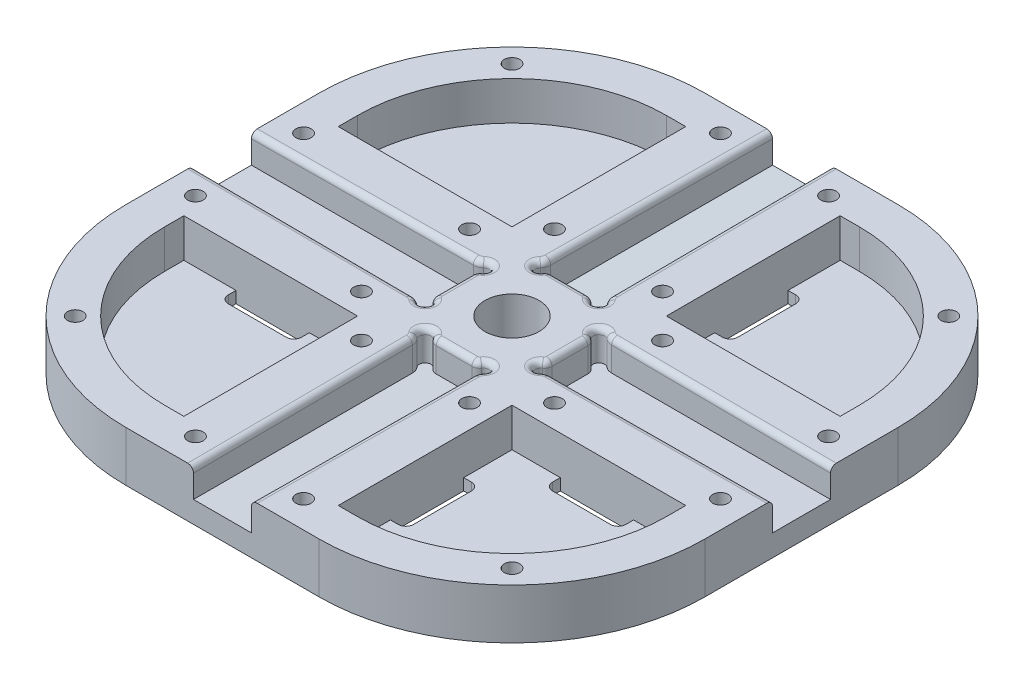
SolidWorks part; units mm, degrees
ref_plane "Front Plane" through (0, 0, 0) normal (0, 0, 1) x (1, 0, 0)
ref_plane "Top Plane" through (0, 0, 0) normal (0, 1, 0) x (1, 0, 0)
ref_plane "Right Plane" through (0, 0, 0) normal (1, 0, 0) x (0, 0, -1)
sketch "Sketch1" plane through (0, 0, 0) normal (0, 1, 0) x (1, 0, 0)
  line L1 (-25, 75) -> (25, 75)
  line L2 (-75, 25) -> (-75, -25)
  line L3 (-25, -75) -> (25, -75)
  line L4 (75, 25) -> (75, -25)
  line L5 (-75, 75) -> (75, -75) construction
  line L6 (-75, -75) -> (75, 75) construction
  arc A0 (-75, -25) -> (-25, -75) centre (-25, -25) ccw
  arc A1 (25, -75) -> (75, -25) centre (25, -25) ccw
  arc A2 (25, 75) -> (75, 25) centre (25, 25) cw
  arc A3 (-25, 75) -> (-75, 25) centre (-25, 25) ccw
  point P0 (0, 0)
  dimension "D3" = 50
  dimension "D1" = 150
  dimension "D2" = 150
extrude "Base-Extrude1" add sketch "Sketch1" along normal blind 13
sketch "Sketch2" plane through (0, 13, 0) normal (0, 1, 0) x (1, 0, 0)
  line L0 (75, 7.5) -> (75, -7.5)
  line L1 (75, 7.5) -> (18.4641, 7.5)
  line L2 (18.4641, 7.5) -> (16.5, 7.5)
  line L3 (0, 75) -> (0, -75) construction
  line L4 (25, 75) -> (-25, 75) construction
  line L5 (-25, -75) -> (25, -75) construction
  line L6 (15, 4.6277) -> (15, -4.6277)
  line L7 (-7.5, 75) -> (7.5, 75)
  line L8 (-7.5, 75) -> (-7.5, 18.4641)
  line L9 (-4.6277, 15) -> (4.6277, 15)
  line L10 (7.5, 75) -> (7.5, 18.4641)
  line L11 (18.4641, -7.5) -> (16.5, -7.5)
  line L12 (75, -7.5) -> (18.4641, -7.5)
  line L13 (7.5, -75) -> (-7.5, -75)
  line L14 (7.5, -75) -> (7.5, -18.4641)
  line L15 (7.5, -18.4641) -> (7.5, -16.5)
  line L16 (4.6277, -15) -> (-4.6277, -15)
  line L17 (-7.5, -18.4641) -> (-7.5, -16.5)
  line L18 (-7.5, -75) -> (-7.5, -18.4641)
  line L19 (-7.5, 18.4641) -> (-7.5, 16.5)
  line L20 (7.5, 18.4641) -> (7.5, 16.5)
  line L21 (-75, -7.5) -> (-75, 7.5)
  line L22 (-75, -7.5) -> (-18.4641, -7.5)
  line L23 (-18.4641, -7.5) -> (-16.5, -7.5)
  line L24 (-15, -4.6277) -> (-15, 4.6277)
  line L25 (-18.4641, 7.5) -> (-16.5, 7.5)
  line L26 (-75, 7.5) -> (-18.4641, 7.5)
  arc A0 (6.269, 14.1429) -> (7.5, 16.5) centre (7.5, 15) ccw
  arc A1 (-6.269, 14.1429) -> (-7.5, 16.5) centre (-7.5, 15) cw
  arc A2 (6.269, 14.1429) -> (4.6277, 15) centre (4.6277, 13) ccw
  arc A3 (14.1429, 6.269) -> (16.5, 7.5) centre (15, 7.5) cw
  arc A4 (14.1429, 6.269) -> (15, 4.6277) centre (13, 4.6277) cw
  arc A5 (-6.269, 14.1429) -> (-4.6277, 15) centre (-4.6277, 13) cw
  arc A6 (14.1429, -6.269) -> (15, -4.6277) centre (13, -4.6277) ccw
  arc A7 (14.1429, -6.269) -> (16.5, -7.5) centre (15, -7.5) ccw
  arc A8 (6.269, -14.1429) -> (7.5, -16.5) centre (7.5, -15) cw
  arc A9 (6.269, -14.1429) -> (4.6277, -15) centre (4.6277, -13) cw
  arc A10 (-6.269, -14.1429) -> (-4.6277, -15) centre (-4.6277, -13) ccw
  arc A11 (-6.269, -14.1429) -> (-7.5, -16.5) centre (-7.5, -15) ccw
  arc A12 (-14.1429, -6.269) -> (-16.5, -7.5) centre (-15, -7.5) cw
  arc A13 (-14.1429, -6.269) -> (-15, -4.6277) centre (-13, -4.6277) cw
  arc A14 (-14.1429, 6.269) -> (-15, 4.6277) centre (-13, 4.6277) ccw
  arc A15 (-14.1429, 6.269) -> (-16.5, 7.5) centre (-15, 7.5) ccw
  point P17 (6, 15)
  point P20 (7.5, 16.5)
  point P23 (-7.5, 16.5)
  point P26 (-6, 15)
  point P69 (0, 0)
  dimension "D3" = 3
  dimension "D4" = 2
  dimension "D1" = 60
  dimension "D2" = 15
  dimension "D5" = 4
extrude "TubePlace-Cut" cut sketch "Sketch2" against normal blind 7.4
draft "Draft3" type of draft neutral plane draft angle 0.4 faces to draft 3 face at (0, 5.6, 29.9571) face at (-7.5, 9.3, 45.75) face at (7.5, 9.3, 45.75) neutral plane through (-25, 13, 75) neutral plane normal (0, 0, 1) reverse direction yes parameters "D1"=0.4
draft "Draft4" type of draft neutral plane draft angle 0.4 faces to draft 3 face at (45.75, 9.3, 7.5) face at (45.75, 9.3, -7.5) face at (29.9571, 5.6, 0) neutral plane through (75, 13, -25) neutral plane normal (1, 0, 0) reverse direction yes parameters "D1"=0.4
draft "Draft5" type of draft neutral plane draft angle 0.4 faces to draft 3 face at (7.5, 9.3, -45.75) face at (0, 5.6, -29.9571) face at (-7.5, 9.3, -45.75) neutral plane through (-25, 13, -75) neutral plane normal (0, 0, -1) reverse direction yes parameters "D1"=0.4
draft "Draft6" type of draft neutral plane draft angle 0.4 faces to draft 3 face at (-29.9571, 5.6, 0) face at (-45.75, 9.3, -7.5) face at (-45.75, 9.3, 7.5) neutral plane through (-75, 13, -25) neutral plane normal (-1, 0, 0) reverse direction yes parameters "D1"=0.4
sketch "Sketch3" plane through (0, 13, 0) normal (0, 1, 0) x (1, 0, 0)
  line L0 (0, 75) -> (0, -75) construction
  line L1 (7.5, 75) -> (-7.5, 75) construction
  line L2 (-7.5, -75) -> (7.5, -75) construction
  line L3 (-75, 0) -> (75, 0) construction
  line L8 (-75, 7.5) -> (-75, -7.5) construction
  line L9 (75, -7.5) -> (75, 7.5) construction
  line L10 (-25, 65) -> (-20, 65)
  line L11 (-20, 65) -> (-20, 20)
  line L14 (-20, 20) -> (-65, 20)
  line L15 (-65, 20) -> (-65, 25)
  line L16 (20, 65) -> (25, 65)
  line L17 (20, 20) -> (20, 65)
  line L18 (65, 20) -> (20, 20)
  line L19 (65, 25) -> (65, 20)
  line L20 (65, -20) -> (65, -25)
  line L21 (20, -20) -> (65, -20)
  line L22 (20, -65) -> (20, -20)
  line L23 (25, -65) -> (20, -65)
  line L24 (-20, -65) -> (-25, -65)
  line L25 (-20, -20) -> (-20, -65)
  line L26 (-65, -20) -> (-20, -20)
  line L27 (-65, -25) -> (-65, -20)
  arc A1 (65, 25) -> (25, 65) centre (25, 25) ccw
  arc A2 (-25, 65) -> (-65, 25) centre (-25, 25) ccw
  arc A3 (-25, 65) -> (-65, 25) centre (-25, 25) ccw
  arc A4 (25, -65) -> (65, -25) centre (25, -25) ccw
  arc A5 (-65, -25) -> (-25, -65) centre (-25, -25) ccw
  circle A6 centre (0, 0) radius 7
  point P39 (0, 0)
  dimension "D5" = 14
  dimension "D2" = 20
  dimension "D3" = 20
  dimension "D1" = 10
  dimension "D4" = 4
extrude "Cut-Extrude2" cut sketch "Sketch3" against normal blind 10
sketch "Sketch4" plane through (0, 3, 0) normal (0, 1, 0) x (1, 0, 0)
  line L0 (-75, 0) -> (75, 0) construction
  line L1 (-75, 7.5) -> (-75, -7.5) construction
  line L2 (75, -7.5) -> (75, 7.5) construction
  line L3 (-22, 49.5) -> (-22, 34.5) construction
  line L4 (-20, 51.5) -> (-20, 32.5)
  line L5 (-24, 49.5) -> (-24, 34.5)
  line L6 (0, 75) -> (0, -75) construction
  line L7 (7.5, 75) -> (-7.5, 75) construction
  line L8 (-7.5, -75) -> (7.5, -75) construction
  line L9 (-20, 20) -> (-20, 65) construction
  line L10 (-22, 51.5) -> (-20, 51.5)
  line L11 (-20, 20) -> (-20, 65) construction
  line L12 (-22, 32.5) -> (-20, 32.5)
  line L13 (0, 0) -> (-53.2843, 53.2843) construction
  line L14 (-51.5, 20) -> (-32.5, 20)
  line L15 (-32.5, 22) -> (-32.5, 20)
  line L16 (-49.5, 24) -> (-34.5, 24)
  line L17 (-51.5, 22) -> (-51.5, 20)
  line L18 (51.5, 22) -> (51.5, 20)
  line L19 (51.5, 20) -> (32.5, 20)
  line L20 (32.5, 22) -> (32.5, 20)
  line L21 (49.5, 24) -> (34.5, 24)
  line L22 (24, 49.5) -> (24, 34.5)
  line L23 (22, 51.5) -> (20, 51.5)
  line L24 (20, 51.5) -> (20, 32.5)
  line L25 (22, 32.5) -> (20, 32.5)
  line L26 (22, -51.5) -> (20, -51.5)
  line L27 (20, -51.5) -> (20, -32.5)
  line L28 (22, -32.5) -> (20, -32.5)
  line L29 (24, -49.5) -> (24, -34.5)
  line L30 (49.5, -24) -> (34.5, -24)
  line L31 (51.5, -22) -> (51.5, -20)
  line L32 (51.5, -20) -> (32.5, -20)
  line L33 (32.5, -22) -> (32.5, -20)
  line L34 (-51.5, -22) -> (-51.5, -20)
  line L35 (-51.5, -20) -> (-32.5, -20)
  line L36 (-32.5, -22) -> (-32.5, -20)
  line L37 (-49.5, -24) -> (-34.5, -24)
  line L38 (-24, -49.5) -> (-24, -34.5)
  line L39 (-22, -51.5) -> (-20, -51.5)
  line L40 (-20, -51.5) -> (-20, -32.5)
  line L41 (-22, -32.5) -> (-20, -32.5)
  arc A0 (-22, 51.5) -> (-24, 49.5) centre (-22, 49.5) ccw
  arc A1 (-24, 34.5) -> (-22, 32.5) centre (-22, 34.5) ccw
  arc A2 (-25, 65) -> (-65, 25) centre (-25, 25) ccw construction
  arc A3 (-34.5, 24) -> (-32.5, 22) centre (-34.5, 22) cw
  arc A4 (-51.5, 22) -> (-49.5, 24) centre (-49.5, 22) cw
  arc A5 (51.5, 22) -> (49.5, 24) centre (49.5, 22) ccw
  arc A6 (34.5, 24) -> (32.5, 22) centre (34.5, 22) ccw
  arc A7 (22, 51.5) -> (24, 49.5) centre (22, 49.5) cw
  arc A8 (24, 34.5) -> (22, 32.5) centre (22, 34.5) cw
  arc A9 (22, -51.5) -> (24, -49.5) centre (22, -49.5) ccw
  arc A10 (24, -34.5) -> (22, -32.5) centre (22, -34.5) ccw
  arc A11 (51.5, -22) -> (49.5, -24) centre (49.5, -22) cw
  arc A12 (34.5, -24) -> (32.5, -22) centre (34.5, -22) cw
  arc A13 (-51.5, -22) -> (-49.5, -24) centre (-49.5, -22) ccw
  arc A14 (-34.5, -24) -> (-32.5, -22) centre (-34.5, -22) ccw
  arc A15 (-22, -51.5) -> (-24, -49.5) centre (-22, -49.5) cw
  arc A16 (-24, -34.5) -> (-22, -32.5) centre (-22, -34.5) cw
  point P89 (0, 0)
  dimension "D3" = 15
  dimension "D5" = 2
  dimension "D6" = 2
  dimension "D1" = 32.5
  dimension "D2" = 4
  dimension "D4" = 2
  dimension "D7" = 2
  dimension "D8" = 4
extrude "Cut-Extrude3" cut sketch "Sketch4" against normal through all
fillet "Fillet1" radius 3 8 edges at (16.4432, 9.0956, 7.9088) (16.4432, 9.0956, -7.9088) (7.9088, 9.0956, 16.4432) (-7.9088, 9.0956, 16.4432) (-16.4432, 9.0956, 7.9088) (-16.4432, 9.0956, -7.9088) (7.9088, 9.0956, -16.4432) (-7.9088, 9.0956, -16.4432)
fillet "Fillet2" radius 1.5 36 edges at (-7.6992, 13, -46.4644) (-8.0916, 13, -16.8904) (-8.4215, 13, -13.8164) (-5.5535, 13, -14.7728) (0, 13, -15) (5.5535, 13, -14.7728) (8.4215, 13, -13.8164) (8.0916, 13, -16.8904) (46.4644, 13, 7.6992) (16.8904, 13, 8.0916) (13.8164, 13, 8.4215) (14.7728, 13, 5.5535) (15, 13, 0) (14.7728, 13, -5.5535) (13.8164, 13, -8.4215) (16.8904, 13, -8.0916) (7.6992, 13, 46.4644) (8.0916, 13, 16.8904) (8.4215, 13, 13.8164) (5.5535, 13, 14.7728) (0, 13, 15) (-5.5535, 13, 14.7728) (-8.4215, 13, 13.8164) (-8.0916, 13, 16.8904) (-46.4644, 13, 7.6992) (-16.8904, 13, 8.0916) (-13.8164, 13, 8.4215) (-14.7728, 13, 5.5535) (-15, 13, 0) (-14.7728, 13, -5.5535) (-13.8164, 13, -8.4215) (-16.8904, 13, -8.0916) (7.6992, 13, -46.4644) (46.4644, 13, -7.6992) (-7.6992, 13, 46.4644) (-46.4644, 13, -7.6992)
sketch "Sketch5" plane through (0, 13, 0) normal (0, 1, 0) x (1, 0, 0)
  line L0 (-14, 75) -> (-14, -75) construction
  line L1 (-9, 75) -> (-25, 75) construction
  line L2 (-25, -75) -> (-9, -75) construction
  line L3 (0, 75) -> (0, -75) construction
  line L4 (7.5, 75) -> (-7.5, 75) construction
  line L5 (-7.5, -75) -> (7.5, -75) construction
  line L6 (-20, 20) -> (-20, 65) construction
  line L7 (0, 0) -> (-75.1792, 75.1792) construction
  line L8 (-75, 0) -> (75, 0) construction
  line L9 (-75, 7.5) -> (-75, -7.5) construction
  line L10 (75, -7.5) -> (75, 7.5) construction
  circle A0 centre (-14, 68) radius 2
  circle A1 centre (-68, 14) radius 2
  circle A2 centre (-56.5685, 56.5685) radius 2
  circle A3 centre (0, 0) radius 80 construction
  circle A4 centre (-14, 25) radius 2
  circle A5 centre (-25, 14) radius 2
  circle A6 centre (56.5685, 56.5685) radius 2
  circle A7 centre (14, 68) radius 2
  circle A8 centre (14, 25) radius 2
  circle A9 centre (25, 14) radius 2
  circle A10 centre (68, 14) radius 2
  circle A11 centre (56.5685, -56.5685) radius 2
  circle A12 centre (68, -14) radius 2
  circle A13 centre (25, -14) radius 2
  circle A14 centre (14, -25) radius 2
  circle A15 centre (14, -68) radius 2
  circle A16 centre (-56.5685, -56.5685) radius 2
  circle A17 centre (-14, -68) radius 2
  circle A18 centre (-14, -25) radius 2
  circle A19 centre (-25, -14) radius 2
  circle A20 centre (-68, -14) radius 2
  point P69 (0, 0)
  dimension "D2" = 4
  dimension "D5" = 4
  dimension "D6" = 160
  dimension "D7" = 4
  dimension "D1" = 6
  dimension "D3" = 7
  dimension "D4" = 45
  dimension "D8" = 25
  dimension "D9" = 4
extrude "Cut-Extrude4" cut sketch "Sketch5" against normal through all
sketch "Sketch6" plane through (0, 0, 0) normal (0, -1, 0) x (1, 0, 0)
  line L0 (-75, 0) -> (75, 0) construction
  line L1 (-75, -25) -> (-75, 25) construction
  line L2 (75, 25) -> (75, -25) construction
  line L3 (0, 75) -> (0, -75) construction
  line L4 (-25, 75) -> (25, 75) construction
  line L5 (25, -75) -> (-25, -75) construction
  circle A0 centre (-14, 68) radius 3.5
  circle A1 centre (-14, 25) radius 3.5
  circle A2 centre (-25, 14) radius 3.5
  circle A3 centre (-56.5685, 56.5685) radius 3.5
  circle A4 centre (-68, 14) radius 3.5
  circle A5 centre (68, 14) radius 3.5
  circle A6 centre (56.5685, 56.5685) radius 3.5
  circle A7 centre (14, 68) radius 3.5
  circle A8 centre (14, 25) radius 3.5
  circle A9 centre (25, 14) radius 3.5
  circle A10 centre (14, -68) radius 3.5
  circle A11 centre (56.5685, -56.5685) radius 3.5
  circle A12 centre (68, -14) radius 3.5
  circle A13 centre (25, -14) radius 3.5
  circle A14 centre (14, -25) radius 3.5
  circle A15 centre (-68, -14) radius 3.5
  circle A16 centre (-56.5685, -56.5685) radius 3.5
  circle A17 centre (-14, -68) radius 3.5
  circle A18 centre (-14, -25) radius 3.5
  circle A19 centre (-25, -14) radius 3.5
  point P60 (0, 0)
  dimension "D1" = 7
  dimension "D2" = 7
  dimension "D3" = 7
  dimension "D4" = 7
  dimension "D5" = 7
  dimension "D6" = 4
extrude "Cut-Extrude5" cut sketch "Sketch6" against normal blind 9
